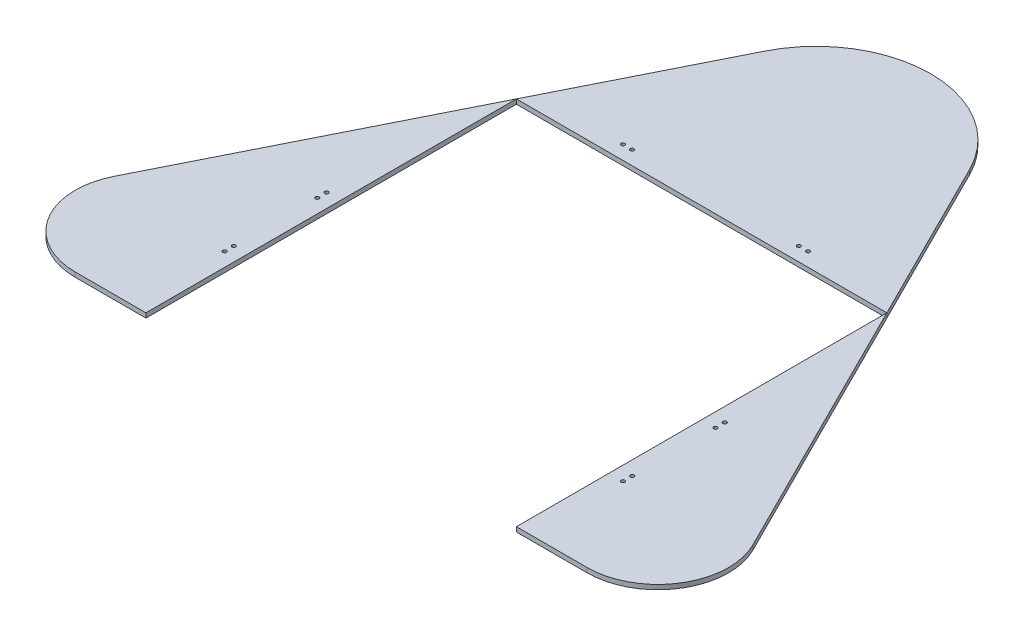
SolidWorks part; units mm, degrees
ref_plane "前视基准面" through (0, 0, 0) normal (0, 0, 1) x (1, 0, 0)
ref_plane "上视基准面" through (0, 0, 0) normal (0, 1, 0) x (1, 0, 0)
ref_plane "右视基准面" through (0, 0, 0) normal (1, 0, 0) x (0, 0, -1)
sketch "草图1" plane through (0, 0, 0) normal (0, 1, 0) x (1, 0, 0)
  line L0 (-390, 390) -> (-5, 390)
  line L1 (-400, 400) -> (400, 400)
  line L2 (-400, 400) -> (-400, -400)
  line L3 (-400, -400) -> (400, -400)
  line L4 (400, 400) -> (400, -400)
  line L5 (0, -400) -> (0, 400) construction
  line L6 (-400, 0) -> (400, 0) construction
  line L7 (390, 390) -> (390, -390)
  line L8 (-390, -390) -> (-5, -390)
  line L9 (-390, 390) -> (-390, -390)
  line L10 (5, -390) -> (5, 390)
  line L11 (-5, -390) -> (-5, 390)
  line L12 (-5, -400) -> (-5, 400) construction
  line L13 (5, -390) -> (390, -390)
  line L14 (-390, -390) -> (390, -390) construction
  line L15 (5, -400) -> (5, 400) construction
  line L16 (5, 390) -> (390, 390)
  line L17 (-390, 390) -> (390, 390) construction
  point P0 (0, 0)
  dimension "D1" = 800
  dimension "D2" = 10
  dimension "D3" = 5
  dimension "D4" = 5
extrude "凸台-拉伸1" add sketch "草图1" along normal blind 200
sketch "草图2" plane through (0, 0, 0) normal (0, -1, 0) x (1, 0, 0)
  line L0 (400, -400) -> (-400, -400) construction
  line L1 (400, 400) -> (400, -400) construction
  line L2 (-400, 400) -> (400, 400) construction
  line L3 (-400, -400) -> (-400, 400) construction
  line L4 (400, -400) -> (-400, -400)
  line L5 (400, 400) -> (400, -400)
  line L6 (-400, 400) -> (400, 400)
  line L7 (-400, -400) -> (-400, 400)
extrude "凸台-拉伸2" add sketch "草图2" against normal blind 10
sketch "草图3" plane through (0, 200, 0) normal (0, 1, 0) x (1, 0, 0)
  line L3 (-400, 400) -> (-400, -400) construction
  line L4 (0, 0) -> (0, -50000) construction
  line L5 (-400, 400) -> (-400, -400)
  line L6 (-400, -400) -> (-552.7864, -400)
  line L7 (-689.4427, -178.8854) -> (-400, 400)
  line L8 (689.4427, -178.8854) -> (400, 400)
  line L9 (400, -400) -> (552.7864, -400)
  line L10 (400, 400) -> (400, -400)
  arc A0 (-689.4427, -178.8854) -> (-552.7864, -400) centre (-552.7864, -247.2136) ccw
  arc A1 (689.4427, -178.8854) -> (552.7864, -400) centre (552.7864, -247.2136) cw
  dimension "D1" = 26.565
extrude "凸台-拉伸3" add sketch "草图3" against normal blind 10 separate body
sketch "草图4" plane through (-400, 0, 0) normal (-1, 0, 0) x (0, 0, 1)
  line L5 (400, 200) -> (400, 0) construction
  line L7 (400, 190) -> (-400, 190) construction
  circle A0 centre (180, 160) radius 4
  circle A1 centre (200, 160) radius 4
  circle A2 centre (-20, 160) radius 4
  circle A3 centre (0, 160) radius 4
  dimension "D1" = 8
  dimension "D3" = 8
  dimension "D2" = 20
  dimension "D4" = 200
  dimension "D5" = 30
  dimension "D6" = 30
  dimension "D7" = 2
  dimension "D8" = 200
sketch "草图5" plane through (0, 200, 0) normal (0, 1, 0) x (1, 0, 0)
  line L0 (-552.7864, -400) -> (-400, -400) construction
  line L2 (-400, 400) -> (-400, -400) construction
  circle A0 centre (-430, -180) radius 4
  circle A1 centre (-430, -200) radius 4
  circle A2 centre (-430, 20) radius 4
  circle A3 centre (-430, 0) radius 4
  dimension "D1" = 8
  dimension "D2" = 8
  dimension "D3" = 20
  dimension "D4" = 200
  dimension "D5" = 30
  dimension "D6" = 30
  dimension "D8" = 200
  dimension "D7" = 2
extrude "切除-拉伸1" cut sketch "草图4" against normal up to next (10 mm away)
extrude "切除-拉伸2" cut sketch "草图5" against normal up to next (10 mm away)
mirror "镜向1" about plane through (0, 0, 0) normal (1, 0, 0) of "切除-拉伸2", "切除-拉伸1"
sketch "草图6" plane through (0, 200, 0) normal (0, 1, 0) x (1, 0, 0)
  line L0 (-400, 400) -> (-221.1146, 757.7709)
  line L2 (221.1146, 757.7709) -> (400, 400)
  line L3 (-689.4427, -178.8854) -> (-400, 400) construction
  line L4 (689.4427, -178.8854) -> (400, 400) construction
  line L5 (400, 400) -> (-400, 400) construction
  line L6 (400, 400) -> (-400, 400)
  arc A0 (221.1146, 757.7709) -> (-221.1146, 757.7709) centre (0, 647.2136) ccw
  dimension "D1" = 247.2136
extrude "凸台-拉伸4" add sketch "草图6" against normal blind 10
sketch "草图7" plane through (0, 0, -400) normal (0, 0, -1) x (-1, 0, 0)
  line L0 (-400, 190) -> (-400, 0) construction
  line L2 (400, 190) -> (-400, 190) construction
  circle A0 centre (-200, 160) radius 4
  circle A1 centre (-180, 160) radius 4
  dimension "D1" = 20
  dimension "D5" = 8
  dimension "D6" = 8
  dimension "D2" = 200
  dimension "D3" = 30
  dimension "D4" = 30
sketch "草图8" plane through (0, 190, 0) normal (0, -1, 0) x (1, 0, 0)
  line L0 (-400, -400) -> (400, -400) construction
  line L1 (400, -400) -> (400, 400) construction
  circle A0 centre (180, -430) radius 4
  circle A1 centre (200, -430) radius 4
  dimension "D1" = 8
  dimension "D2" = 8
  dimension "D3" = 20
  dimension "D4" = 30
  dimension "D5" = 30
  dimension "D6" = 200
extrude "切除-拉伸3" cut sketch "草图7" against normal up to next
extrude "切除-拉伸4" cut sketch "草图8" against normal up to next
mirror "镜向2" about plane through (0, 0, 0) normal (1, 0, 0) of "切除-拉伸4", "切除-拉伸3"
sketch "草图9" plane through (0, 0, 0) normal (0, -1, 0) x (1, 0, 0)
  line L4 (400, -400) -> (400, 400)
  line L5 (400, 400) -> (-400, 400)
  line L6 (-400, 400) -> (-400, -400)
  line L7 (-400, -400) -> (400, -400)
  line L8 (400, -400) -> (400, 400)
  line L9 (400, 400) -> (-400, 400)
  line L10 (-400, 400) -> (-400, -400)
  line L11 (-400, -400) -> (400, -400)
  dimension "D1" = 0
extrude "切除-拉伸5" cut sketch "草图9" against normal through all
